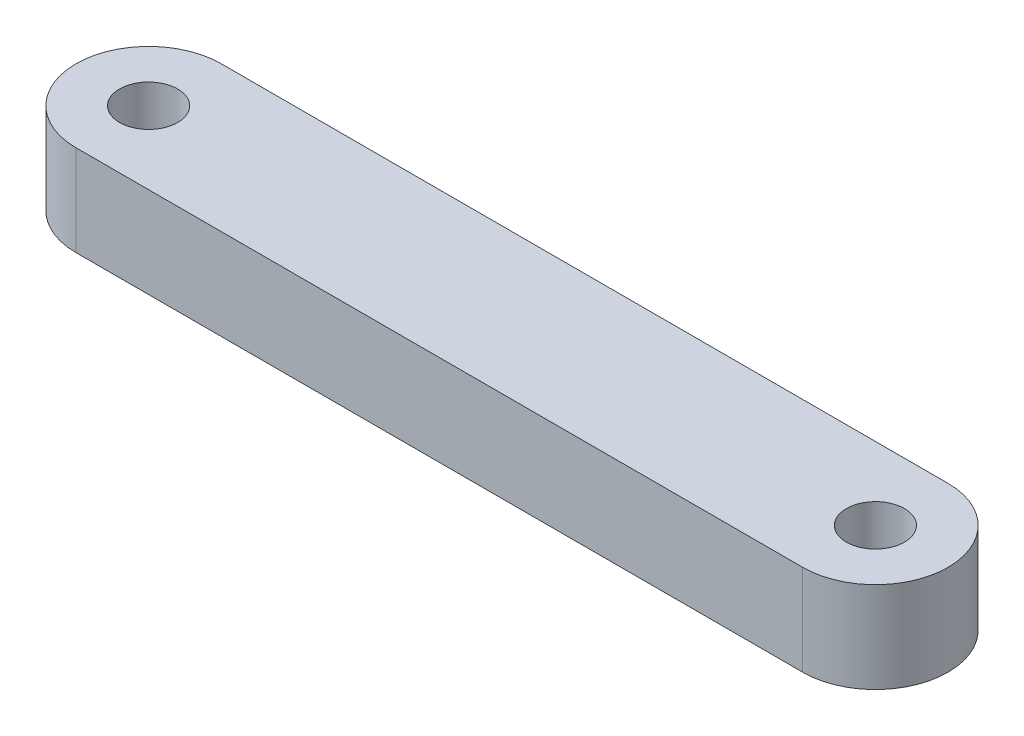
SolidWorks part; units mm, degrees
ref_plane "Plan de face" through (0, 0, 0) normal (0, 0, 1) x (1, 0, 0)
ref_plane "Plan de dessus" through (0, 0, 0) normal (0, 1, 0) x (1, 0, 0)
ref_plane "Plan de droite" through (0, 0, 0) normal (1, 0, 0) x (0, 0, -1)
sketch "Esquisse1" plane through (0, 0, 0) normal (0, 1, 0) x (1, 0, 0)
  line L0 (0, 4) -> (0, -4) construction
  line L1 (-24, 0) -> (24, 0) construction
  line L2 (20, 0) -> (-20, 0) construction
  line L3 (20, -4) -> (-20, -4)
  line L4 (20, 4) -> (-20, 4)
  arc A0 (20, -4) -> (20, 4) centre (20, 0) ccw
  arc A1 (-20, 4) -> (-20, -4) centre (-20, 0) ccw
  circle A2 centre (-20, 0) radius 1.6
  circle A3 centre (20, 0) radius 1.6
  point P7 (0, 0)
  dimension "D3" = 3.2
  dimension "D1" = 8
  dimension "D2" = 40
  dimension "D4" = 20
  dimension "D5" = 20
extrude "Boss.-Extru.1" add sketch "Esquisse1" along normal blind 5
